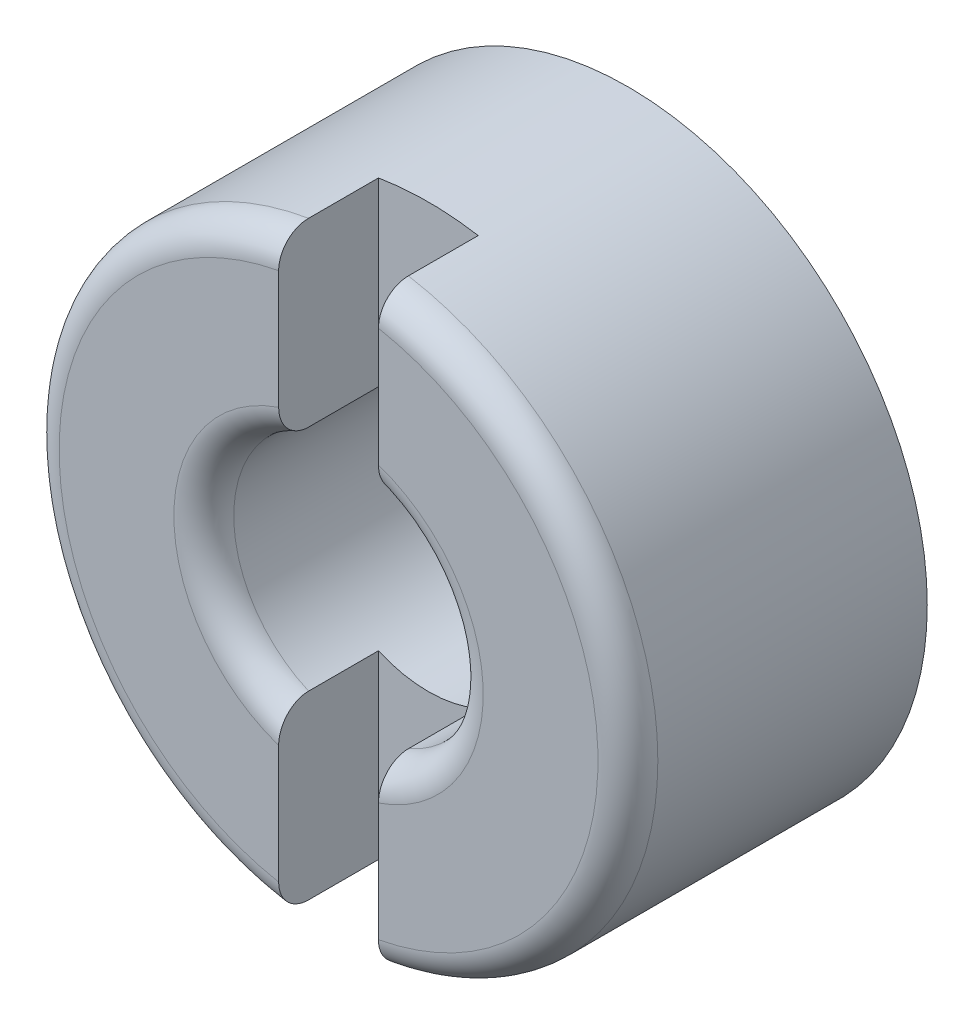
SolidWorks part; units mm, degrees
ref_plane "Front Plane" through (0, 0, 0) normal (0, 0, 1) x (1, 0, 0)
ref_plane "Top Plane" through (0, 0, 0) normal (0, 1, 0) x (1, 0, 0)
ref_plane "Right Plane" through (0, 0, 0) normal (1, 0, 0) x (0, 0, -1)
sketch "Sketch1" plane through (0, 0, 0) normal (0, 0, 1) x (1, 0, 0)
  line L0 (0, 0) -> (0, 0.2196) construction
  circle A0 centre (0, 0) radius 3
  dimension "D1" = 6
extrude "Boss-Extrude1" add sketch "Sketch1" along normal blind 3
sketch "Sketch2" plane through (0, 0, 3) normal (0, 0, 1) x (1, 0, 0)
  circle A0 centre (0, 0) radius 1.25
  dimension "D1" = 2.5
extrude "Cut-Extrude1" cut sketch "Sketch2" against normal through all
fillet "Fillet1" radius 0.3 3 edges at (1.25, 0, 0) (3, 0, 3) (1.25, 0, 3)
sketch "Sketch3" plane through (0, 0, 3) normal (0, 0, 1) x (1, 0, 0)
  line L0 (0, 0) -> (0, 4.6634) construction
  line L2 (-0.5, -4) -> (0.5, -4)
  line L3 (-0.5, -4) -> (-0.5, 4)
  line L4 (-0.5, 4) -> (0.5, 4)
  line L5 (0.5, -4) -> (0.5, 4)
  line L6 (-0.5, -4) -> (0.5, 4) construction
  line L7 (-0.5, 4) -> (0.5, -4) construction
  point P1 (0, 0)
  dimension "D1" = 1
  dimension "D2" = 4
extrude "Cut-Extrude3" cut sketch "Sketch3" against normal blind 1
